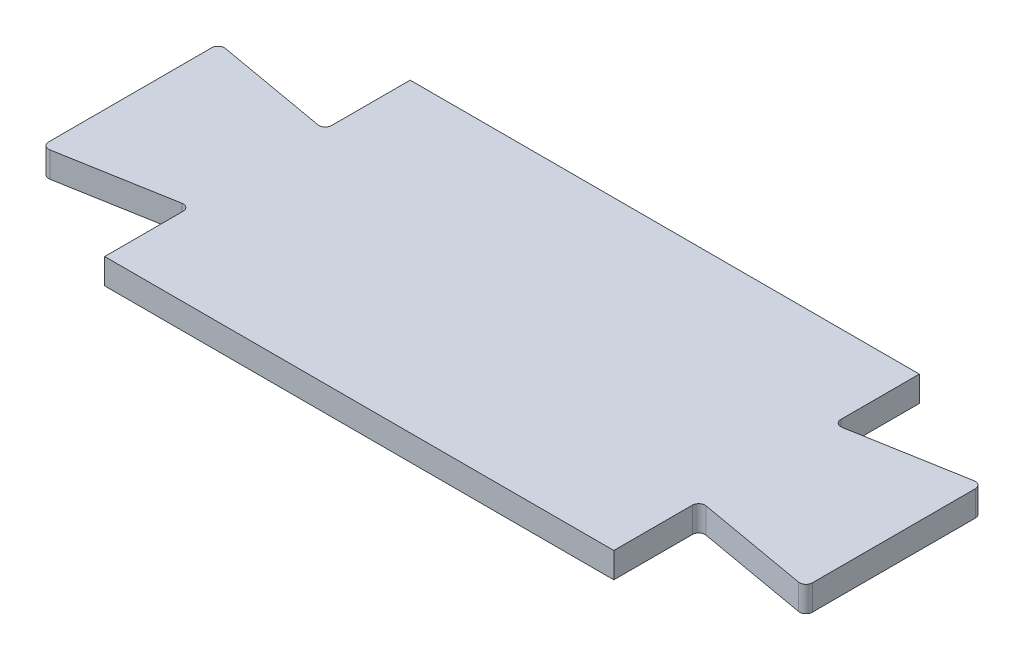
SolidWorks part; units mm, degrees
ref_plane "Front Plane" through (0, 0, 0) normal (0, 0, 1) x (1, 0, 0)
ref_plane "Top Plane" through (0, 0, 0) normal (0, 1, 0) x (1, 0, 0)
ref_plane "Right Plane" through (0, 0, 0) normal (1, 0, 0) x (0, 0, -1)
sketch "Sketch1" plane through (0, 0, 0) normal (0, 1, 0) x (1, 0, 0)
  line L0 (-10, 2.6184) -> (-15, 3.5)
  line L1 (-10, -6) -> (10, -6)
  line L2 (-10, -6) -> (-10, -2.6184)
  line L3 (-10, 6) -> (10, 6)
  line L4 (10, -6) -> (10, -2.6184)
  line L5 (-10, -6) -> (10, 6) construction
  line L6 (-10, 6) -> (10, -6) construction
  line L7 (-15, 3.5) -> (-15, -3.5)
  line L8 (-10, 0) -> (-18.3718, 0) construction
  line L9 (-10, -2.6184) -> (-15, -3.5)
  line L10 (-10, 2.6184) -> (-10, 6)
  line L11 (0, 0) -> (0, 6) construction
  line L12 (10, -2.6184) -> (15, -3.5)
  line L13 (15, 3.5) -> (15, -3.5)
  line L14 (10, 2.6184) -> (15, 3.5)
  line L15 (10, 2.6184) -> (10, 6)
  line L16 (-10, 6) -> (-20.4194, 6) construction
  point P0 (0, 0)
  point P13 (-15, 0)
  dimension "D1" = 12
  dimension "D2" = 20
  dimension "D3" = 3.5
  dimension "D4" = 80
  dimension "D5" = 5
extrude "Boss-Extrude1" add sketch "Sketch1" along normal blind 1
fillet "Fillet1" radius 0.25 8 edges at (-10, 0.5, 2.6184) (-15, 0.5, 3.5) (-15, 0.5, -3.5) (-10, 0.5, -2.6184) (10, 0.5, -2.6184) (15, 0.5, -3.5) (15, 0.5, 3.5) (10, 0.5, 2.6184)
